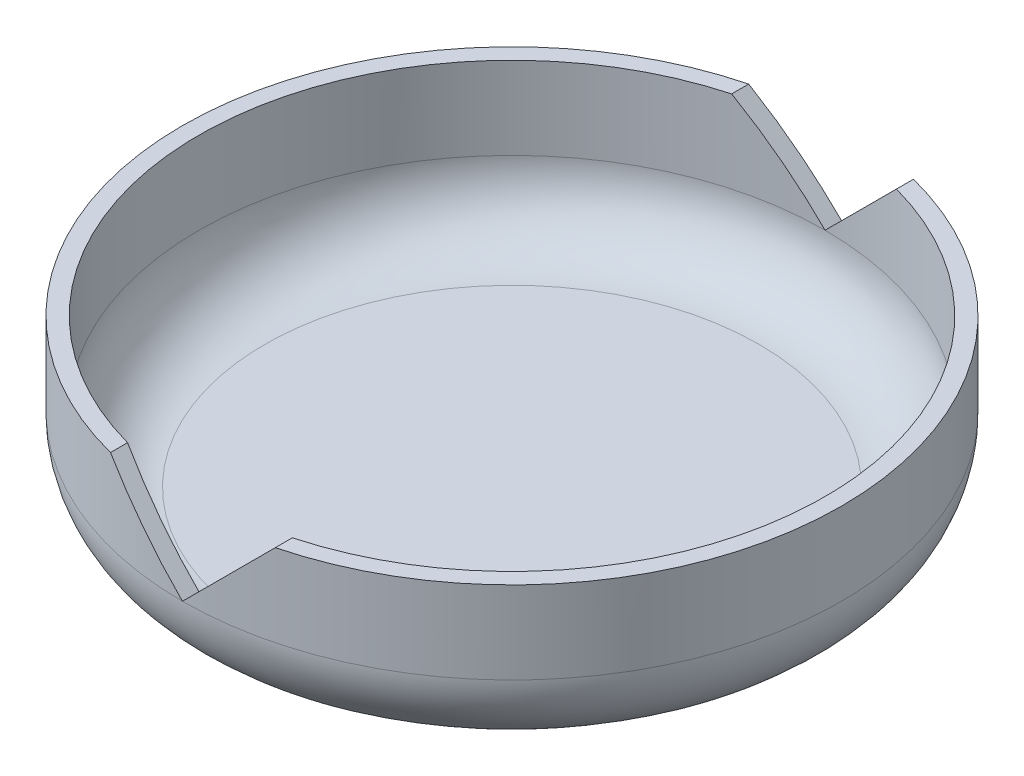
SolidWorks part; units mm, degrees
ref_plane "Front Plane" through (0, 0, 0) normal (0, 0, 1) x (1, 0, 0)
ref_plane "Top Plane" through (0, 0, 0) normal (0, 1, 0) x (1, 0, 0)
ref_plane "Right Plane" through (0, 0, 0) normal (1, 0, 0) x (0, 0, -1)
sketch "Sketch1" plane through (0, 0, 0) normal (0, 1, 0) x (1, 0, 0)
  circle A0 centre (0, 0) radius 40
  dimension "D1" = 80
extrude "Boss-Extrude1" add sketch "Sketch1" along normal blind 20
fillet "Fillet1" radius 10 1 edges at (0, 0, 40)
shell "Shell1" thickness 2
sketch "Sketch2" plane through (0, 0, 0) normal (0, 0, 1) x (1, 0, 0)
  line L0 (-17.4587, 27.4587) -> (0, 10)
  line L1 (0, 10) -> (20.2798, 30.2798)
  line L2 (20.2798, 30.2798) -> (-17.4587, 27.4587)
  line L3 (-30, 0) -> (30, 0) construction
  dimension "D1" = 10
  dimension "D2" = 45
extrude "Cut-Extrude1" cut sketch "Sketch2" against normal through all both and the other way through all
